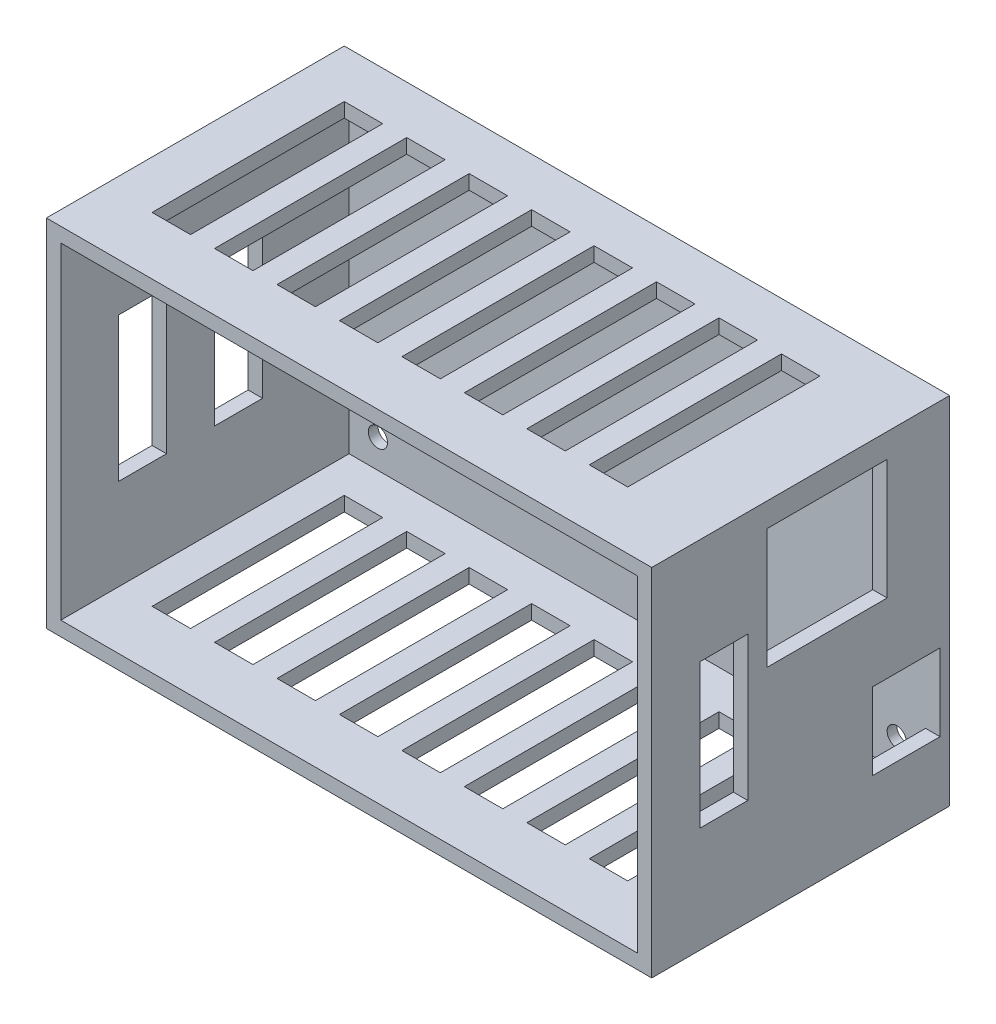
SolidWorks part; units mm, degrees
ref_plane "Plano frontal" through (0, 0, 0) normal (0, 0, 1) x (1, 0, 0)
ref_plane "Plano superior" through (0, 0, 0) normal (0, 1, 0) x (1, 0, 0)
ref_plane "Plano direito" through (0, 0, 0) normal (1, 0, 0) x (0, 0, -1)
sketch "Esboço1" plane through (0, 0, 0) normal (0, 0, 1) x (1, 0, 0)
  line L0 (-63, 37) -> (63, 37)
  line L1 (-60, 34) -> (60, 34)
  line L2 (-60, 34) -> (-60, -34)
  line L3 (-60, -34) -> (60, -34)
  line L4 (60, 34) -> (60, -34)
  line L5 (-60, 34) -> (60, -34) construction
  line L6 (-60, -34) -> (60, 34) construction
  line L7 (63, 37) -> (63, -37)
  line L8 (-63, -37) -> (63, -37)
  line L9 (-63, 37) -> (-63, -37)
  point P0 (0, 0)
  dimension "D2" = 120
  dimension "D3" = 68
  dimension "D1" = 3
extrude "Ressalto-extrusão1" add sketch "Esboço1" along normal blind 60
sketch "Esboço2" plane through (0, 0, 0) normal (0, 0, -1) x (-1, 0, 0)
  line L0 (-63, -37) -> (-63, 37) construction
  line L1 (63, -37) -> (-63, -37) construction
  line L2 (-63, 37) -> (63, 37) construction
  line L3 (63, 37) -> (63, -37) construction
  line L4 (-63, -37) -> (-63, 37)
  line L5 (63, -37) -> (-63, -37)
  line L6 (-63, 37) -> (63, 37)
  line L7 (63, 37) -> (63, -37)
  line L8 (54, 28) -> (-54, 28) construction
  line L9 (-54, 28) -> (-54, -28) construction
  line L10 (-54, -28) -> (54, -28) construction
  line L11 (54, -28) -> (54, 28) construction
  line L12 (54, 0) -> (60, 0) construction
  line L13 (60, 34) -> (60, -34) construction
  line L14 (0, 28) -> (0, 34) construction
  line L15 (-60, 34) -> (60, 34) construction
  line L16 (-54, 0) -> (-60, 0) construction
  line L17 (-60, -34) -> (-60, 34) construction
  line L18 (0, -28) -> (0, -34) construction
  line L19 (60, -34) -> (-60, -34) construction
  circle A0 centre (-54, -28) radius 2
  circle A1 centre (54, -28) radius 2
  circle A2 centre (54, 28) radius 2
  circle A3 centre (-54, 28) radius 2
  dimension "D1" = 4
  dimension "D2" = 6
extrude "Ressalto-extrusão2" add sketch "Esboço2" along normal blind 2
sketch "Esboço3" plane through (63, 0, 0) normal (1, 0, 0) x (0, 0, -1)
  line L0 (-60, -37) -> (2, -37) construction
  line L1 (-36, 32) -> (-11, 32)
  line L2 (-36, 32) -> (-36, 7)
  line L3 (-36, 7) -> (-11, 7)
  line L4 (-11, 32) -> (-11, 7)
  line L5 (-14, -7.5) -> (0, -7.5)
  line L6 (-14, -7.5) -> (-14, -23.5)
  line L7 (-14, -23.5) -> (0, -23.5)
  line L8 (0, -7.5) -> (0, -23.5)
  line L9 (2, 37) -> (2, -37) construction
  line L10 (-60, 37) -> (2, 37) construction
  line L11 (-60, -37) -> (-60, 37) construction
  line L12 (-50, 15) -> (-40, 15)
  line L13 (-50, 15) -> (-50, -15)
  line L14 (-50, -15) -> (-40, -15)
  line L15 (-40, 15) -> (-40, -15)
  line L16 (-50, 15) -> (-40, -15) construction
  line L17 (-50, -15) -> (-40, 15) construction
  point P14 (-45, 0)
  point P19 (-38.4129, -1.3899)
  point P23 (-60, 0)
  dimension "D1" = 16
  dimension "D2" = 14
  dimension "D3" = 13.5
  dimension "D4" = 2
  dimension "D5" = 25
  dimension "D6" = 25
  dimension "D7" = 5
  dimension "D8" = 13
  dimension "D9" = 15
  dimension "D10" = 30
  dimension "D11" = 10
extrude "Corte-extrusão1" cut sketch "Esboço3" against normal blind 10
sketch "Esboço6" plane through (0, -37, 0) normal (0, -1, 0) x (1, 0, 0)
  line L0 (63, -2) -> (-63, -2) construction
  line L1 (-53, 48) -> (-45, 48)
  line L2 (-53, 48) -> (-53, 8)
  line L3 (-53, 8) -> (-45, 8)
  line L4 (-45, 48) -> (-45, 8)
  line L5 (-63, 60) -> (-63, -2) construction
  line L6 (-40, 48) -> (-32, 48)
  line L7 (-40, 48) -> (-40, 8)
  line L8 (-40, 8) -> (-32, 8)
  line L9 (-32, 48) -> (-32, 8)
  line L10 (-27, 48) -> (-19, 48)
  line L11 (-27, 48) -> (-27, 8)
  line L12 (-27, 8) -> (-19, 8)
  line L13 (-19, 48) -> (-19, 8)
  line L14 (-14, 48) -> (-6, 48)
  line L15 (-14, 48) -> (-14, 8)
  line L16 (-14, 8) -> (-6, 8)
  line L17 (-6, 48) -> (-6, 8)
  line L18 (-1, 48) -> (7, 48)
  line L19 (-1, 48) -> (-1, 8)
  line L20 (-1, 8) -> (7, 8)
  line L21 (7, 48) -> (7, 8)
  line L22 (12, 48) -> (20, 48)
  line L23 (12, 48) -> (12, 8)
  line L24 (12, 8) -> (20, 8)
  line L25 (20, 48) -> (20, 8)
  line L26 (25, 48) -> (33, 48)
  line L27 (25, 48) -> (25, 8)
  line L28 (25, 8) -> (33, 8)
  line L29 (33, 48) -> (33, 8)
  line L30 (38, 48) -> (46, 48)
  line L31 (38, 48) -> (38, 8)
  line L32 (38, 8) -> (46, 8)
  line L33 (46, 48) -> (46, 8)
  dimension "D1" = 8
  dimension "D2" = 40
  dimension "D3" = 10
  dimension "D4" = 10
  dimension "D5" = 8
extrude "Corte-extrusão2" cut sketch "Esboço6" against normal through all
sketch "Esboço7" plane through (-63, 0, 0) normal (-1, 0, 0) x (0, 0, 1)
  line L0 (-2, -37) -> (-2, 37) construction
  line L1 (48, 15) -> (38, 15)
  line L2 (48, 15) -> (48, -15)
  line L3 (48, -15) -> (38, -15)
  line L4 (38, 15) -> (38, -15)
  line L5 (48, 15) -> (38, -15) construction
  line L6 (48, -15) -> (38, 15) construction
  line L7 (28, 15) -> (18, 15)
  line L8 (28, 15) -> (28, -15)
  line L9 (28, -15) -> (18, -15)
  line L10 (18, 15) -> (18, -15)
  line L11 (28, 15) -> (18, -15) construction
  line L12 (28, -15) -> (18, 15) construction
  point P0 (43, 0)
  point P5 (23, 0)
  point P10 (0, 0)
  dimension "D1" = 10
  dimension "D2" = 30
  dimension "D3" = 10
  dimension "D4" = 20
extrude "Corte-extrusão3" cut sketch "Esboço7" against normal blind 12
